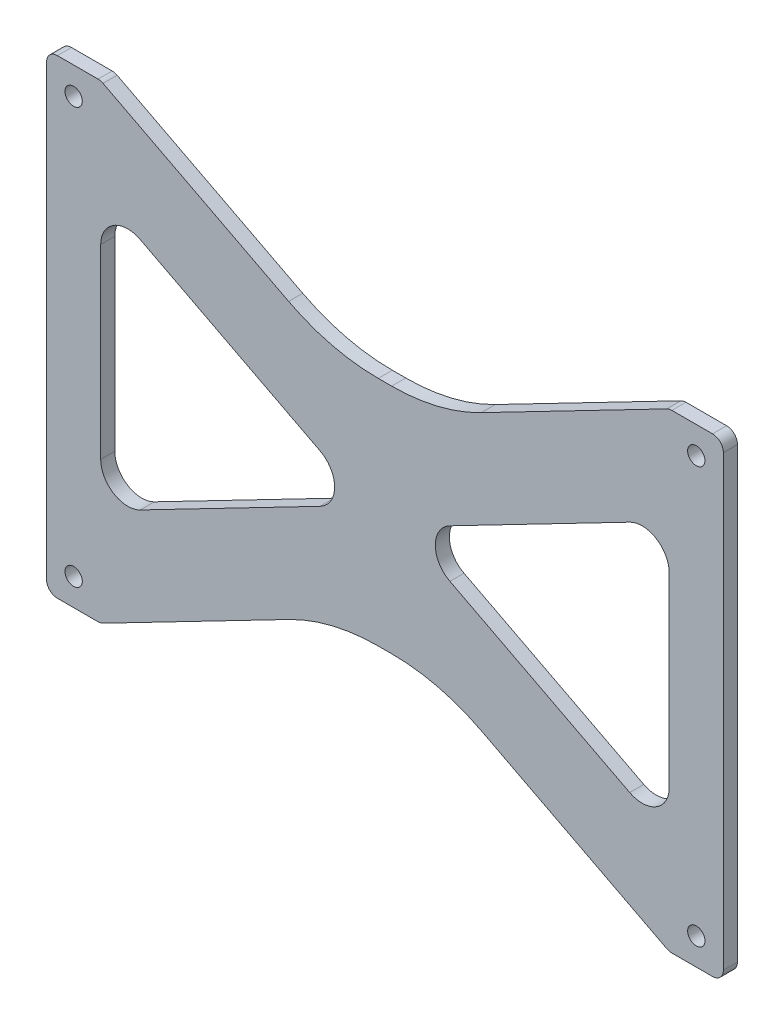
SolidWorks part; units mm, degrees
ref_plane "Front Plane" through (0, 0, 0) normal (0, 0, 1) x (1, 0, 0)
ref_plane "Top Plane" through (0, 0, 0) normal (0, 1, 0) x (1, 0, 0)
ref_plane "Right Plane" through (0, 0, 0) normal (1, 0, 0) x (0, 0, -1)
sketch "Sketch1" plane through (0, 0, 0) normal (0, 0, 1) x (1, 0, 0)
  line L0 (0, -57.6358) -> (0, 84.166) construction
  line L1 (11.43, 68.9225) -> (-79.375, 68.9225) construction
  line L2 (-79.375, 68.9225) -> (-79.375, -41.3135)
  line L3 (-79.375, -41.3135) -> (11.43, -41.3135) construction
  line L4 (-79.375, -41.3135) -> (-66.675, -41.3135)
  line L5 (-79.375, 68.9225) -> (-66.675, 68.9225)
  line L6 (-79.375, 13.8045) -> (112.395, 13.8045) construction
  line L7 (79.375, -41.3135) -> (66.675, -41.3135)
  line L8 (79.375, 68.9225) -> (79.375, -41.3135)
  line L9 (79.375, 68.9225) -> (66.675, 68.9225)
  line L10 (-66.675, -41.3135) -> (-12.7, -13.3807)
  line L11 (-12.7, -13.3807) -> (12.7, -13.3807)
  line L12 (-12.7, 40.9898) -> (12.7, 40.9898)
  line L13 (-66.675, 68.9225) -> (-12.7, 40.9898)
  line L14 (66.675, -41.3135) -> (12.7, -13.3807)
  line L15 (66.675, 68.9225) -> (12.7, 40.9898)
  circle A0 centre (-73.025, 62.5725) radius 2.032
  circle A2 centre (-73.025, -34.9635) radius 2.032
  circle A3 centre (73.025, -34.9635) radius 2.032
  circle A4 centre (73.025, 62.5725) radius 2.032
  point P23 (0, -13.3807)
  point P29 (0, 40.9898)
  dimension "D3" = 4.064
  dimension "D1" = 97.536
  dimension "D2" = 6.35
  dimension "D4" = 6.35
  dimension "D5" = 79.375
  dimension "D6" = 6.35
  dimension "D7" = 25.4
  dimension "D8" = 11.43
  dimension "D9" = 66.675
  dimension "D10" = 13.8045
  dimension "D11" = 40.9898
extrude "Boss-Extrude1" add sketch "Sketch1" along normal blind 3.302
fillet "Fillet1" radius 45.72 4 edges at (12.7, 40.9898, 1.651) (-12.7, 40.9898, 1.651) (12.7, -13.3807, 1.651) (-12.7, -13.3807, 1.651)
fillet "Fillet2" radius 2.54 8 edges at (-66.675, 68.9225, 1.651) (66.675, 68.9225, 1.651) (-66.675, -41.3135, 1.651) (66.675, -41.3135, 1.651) (79.375, -41.3135, 1.651) (79.375, 68.9225, 1.651) (-79.375, 68.9225, 1.651) (-79.375, -41.3135, 1.651)
sketch "Sketch2" plane through (0, 0, 3.302) normal (0, 0, 1) x (1, 0, 0)
  line L0 (-79.375, 13.8045) -> (79.375, 13.8045) construction
  line L3 (-79.375, 66.3825) -> (-79.375, -38.7735) construction
  line L4 (79.375, -38.7735) -> (79.375, 66.3825) construction
  line L5 (-66.675, 46.0625) -> (-66.675, -18.4535)
  line L6 (-76.835, -41.3135) -> (-67.2933, -41.3135) construction
  line L7 (-66.675, -18.4535) -> (-4.3423, 13.8045)
  line L8 (-66.1259, -41.0293) -> (-22.5842, -18.4959) construction
  line L9 (-66.675, 46.0625) -> (-4.3423, 13.8045)
  line L10 (0, -29.0797) -> (0, 60.2744) construction
  line L11 (66.675, 46.0625) -> (66.675, -18.4535)
  line L12 (66.675, -18.4535) -> (4.3423, 13.8045)
  line L13 (66.675, 46.0625) -> (4.3423, 13.8045)
  point P16 (-66.675, 13.8045)
  dimension "D1" = 22.86
  dimension "D2" = 12.7
extrude "Cut-Extrude1" cut sketch "Sketch2" against normal through all
fillet "Fillet3" radius 6.35 6 edges at (66.675, -18.4535, 1.651) (66.675, 46.0625, 1.651) (4.3423, 13.8045, 1.651) (-4.3423, 13.8045, 1.651) (-66.675, 46.0625, 1.651) (-66.675, -18.4535, 1.651)
